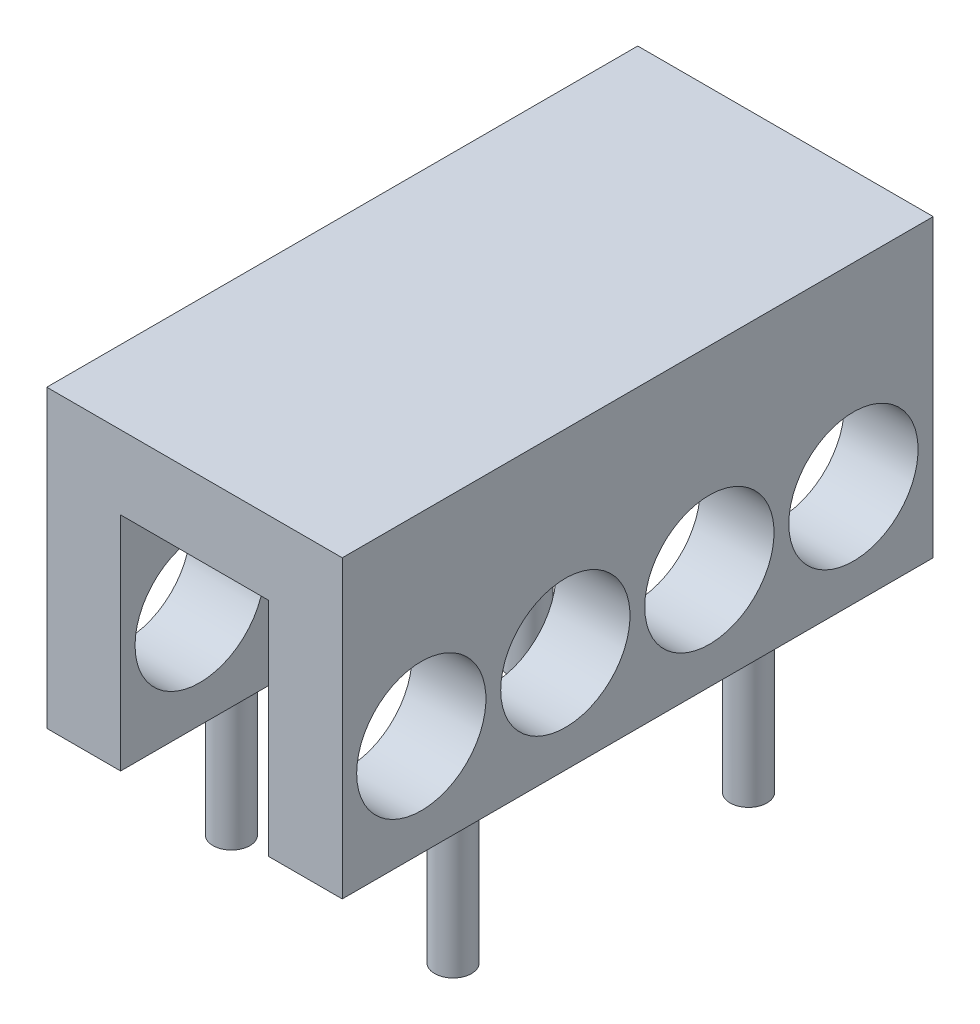
SolidWorks part; units mm, degrees
ref_plane "Front Plane" through (0, 0, 0) normal (0, 0, 1) x (1, 0, 0)
ref_plane "Top Plane" through (0, 0, 0) normal (0, 1, 0) x (1, 0, 0)
ref_plane "Right Plane" through (0, 0, 0) normal (1, 0, 0) x (0, 0, -1)
sketch "Sketch4" plane through (0, 0, 0) normal (0, 0, 1) x (1, 0, 0)
  line L0 (0, 0) -> (0, 50.8)
  line L1 (0, 50.8) -> (50.8, 50.8)
  line L2 (50.8, 50.8) -> (50.8, 0)
  line L3 (50.8, 0) -> (38.1, 0)
  line L4 (38.1, 0) -> (38.1, 38.136)
  line L5 (38.1, 38.136) -> (12.7, 38.136)
  line L6 (12.7, 38.136) -> (12.7, 0)
  line L7 (12.7, 0) -> (0, 0)
  dimension "D1" = 50.8
  dimension "D2" = 50.8
  dimension "D3" = 25.4
  dimension "D4" = 12.7
extrude "Boss-Extrude1" add sketch "Sketch4" along normal blind 101.6
sketch "Sketch5" plane through (0, 0, 0) normal (-1, 0, 0) x (0, 0, 1)
  line L0 (0, 50.8) -> (0, 0) construction
  line L1 (101.6, 0) -> (0, 0) construction
  circle A0 centre (13.716, 17.4625) radius 11.1125
  circle A1 centre (38.481, 17.4625) radius 11.1125
  circle A2 centre (63.246, 17.4625) radius 11.1125
  circle A3 centre (88.011, 17.4625) radius 11.1125
  dimension "D1" = 22.225
  dimension "D2" = 13.716
  dimension "D3" = 24.765
  dimension "D4" = 24.765
  dimension "D5" = 24.765
  dimension "D6" = 17.4625
extrude "Cut-Extrude1" cut sketch "Sketch5" against normal through all
sketch "Sketch6" plane through (0, 0, 0) normal (0, -1, 0) x (1, 0, 0)
  line L0 (0, 101.6) -> (0, 0) construction
  line L1 (50.8, 101.6) -> (50.8, 0) construction
  line L2 (0, 0) -> (12.7, 0) construction
  line L3 (38.1, 0) -> (50.8, 0) construction
  circle A0 centre (6.35, 25.4) radius 3.175
  circle A1 centre (6.35, 76.2) radius 3.175
  circle A2 centre (44.45, 76.2) radius 3.175
  circle A3 centre (44.45, 25.4) radius 3.175
  dimension "D1" = 6.35
  dimension "D2" = 6.35
  dimension "D3" = 6.35
  dimension "D4" = 6.35
  dimension "D5" = 6.35
  dimension "D6" = 6.35
  dimension "D7" = 6.35
  dimension "D8" = 6.35
  dimension "D9" = 50.8
  dimension "D10" = 25.4
  dimension "D11" = 50.8
  dimension "D12" = 25.4
extrude "Boss-Extrude3" add sketch "Sketch6" along normal blind 25.4
